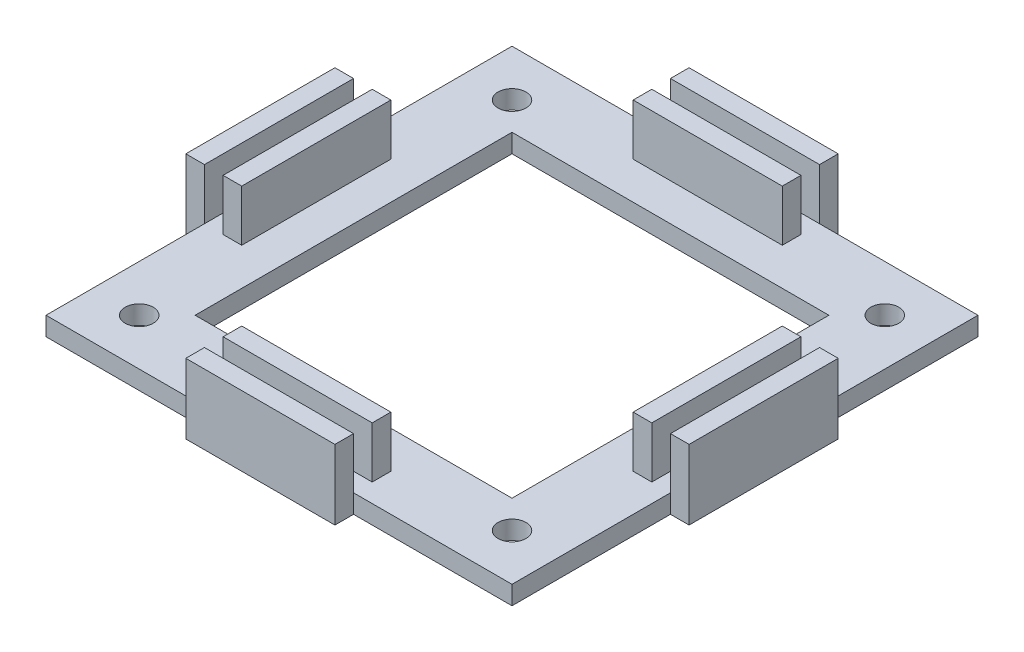
SolidWorks part; units mm, degrees
ref_plane "Front Plane" through (0, 0, 0) normal (0, 0, 1) x (1, 0, 0)
ref_plane "Top Plane" through (0, 0, 0) normal (0, 1, 0) x (1, 0, 0)
ref_plane "Right Plane" through (0, 0, 0) normal (1, 0, 0) x (0, 0, -1)
sketch "Sketch1" plane through (0, 0, 0) normal (0, 1, 0) x (1, 0, 0)
  line L1 (-25, -25) -> (25, -25)
  line L2 (-25, -25) -> (-25, 25)
  line L3 (-25, 25) -> (25, 25)
  line L4 (25, -25) -> (25, 25)
  line L5 (-25, -25) -> (25, 25) construction
  line L6 (-25, 25) -> (25, -25) construction
  line L7 (-17, -17) -> (17, -17)
  line L8 (-17, -17) -> (-17, 17)
  line L9 (-17, 17) -> (17, 17)
  line L10 (17, -17) -> (17, 17)
  line L11 (-17, -17) -> (17, 17) construction
  line L12 (-17, 17) -> (17, -17) construction
  point P0 (0, 0)
  point P6 (0, 0)
  dimension "D1" = 50
  dimension "D2" = 8
extrude "Boss-Extrude1" add sketch "Sketch1" along normal blind 2
sketch "Sketch2" plane through (0, 2, 0) normal (0, 1, 0) x (1, 0, 0)
  line L1 (-20, -20) -> (20, -20) construction
  line L2 (-20, -20) -> (-20, 20) construction
  line L3 (-20, 20) -> (20, 20) construction
  line L4 (20, -20) -> (20, 20) construction
  line L5 (-20, -20) -> (20, 20) construction
  line L6 (-20, 20) -> (20, -20) construction
  circle A0 centre (-20, 20) radius 1.5
  circle A1 centre (20, 20) radius 1.5
  circle A2 centre (20, -20) radius 1.5
  circle A3 centre (-20, -20) radius 1.5
  point P0 (0, 0)
  dimension "D2" = 3
  dimension "D1" = 40
extrude "Cut-Extrude1" cut sketch "Sketch2" against normal up to surface (2 mm away) up to face at (0, 0, 0)
sketch "Sketch7" plane through (0, 0, 0) normal (0, 1, 0) x (1, 0, 0)
  line L0 (8, 23) -> (-8, 23)
  line L5 (-25, 25) -> (-25, -25) construction
  line L6 (-25, 8) -> (-27, 8)
  line L7 (-25, 8) -> (-25, -8)
  line L8 (-25, -8) -> (-27, -8)
  line L9 (-27, 8) -> (-27, -8)
  line L10 (8, 23) -> (8, 21)
  line L11 (-23, 8) -> (-21, 8)
  line L12 (-23, 8) -> (-23, -8)
  line L13 (-23, -8) -> (-21, -8)
  line L14 (-21, 8) -> (-21, -8)
  line L15 (8, 21) -> (-8, 21)
  line L16 (-8, 23) -> (-8, 21)
  line L17 (8, 25) -> (-8, 25)
  line L18 (8, 25) -> (8, 27)
  line L19 (8, 27) -> (-8, 27)
  line L20 (-8, 25) -> (-8, 27)
  line L21 (23, -8) -> (23, 8)
  line L22 (23, -8) -> (21, -8)
  line L23 (21, -8) -> (21, 8)
  line L24 (23, 8) -> (21, 8)
  line L25 (25, -8) -> (25, 8)
  line L26 (25, -8) -> (27, -8)
  line L27 (27, -8) -> (27, 8)
  line L28 (25, 8) -> (27, 8)
  line L29 (-8, -23) -> (8, -23)
  line L30 (-8, -23) -> (-8, -21)
  line L31 (-8, -21) -> (8, -21)
  line L32 (8, -23) -> (8, -21)
  line L33 (-8, -25) -> (8, -25)
  line L34 (-8, -25) -> (-8, -27)
  line L35 (-8, -27) -> (8, -27)
  line L36 (8, -25) -> (8, -27)
  point P10 (-25, 0)
  point P11 (-23, 0)
  point P40 (0, 0)
  dimension "D1" = 2
  dimension "D2" = 2
  dimension "D3" = 2
  dimension "D4" = 16
  dimension "D5" = 4
extrude "Boss-Extrude4" add sketch "Sketch7" along normal blind 7.5
